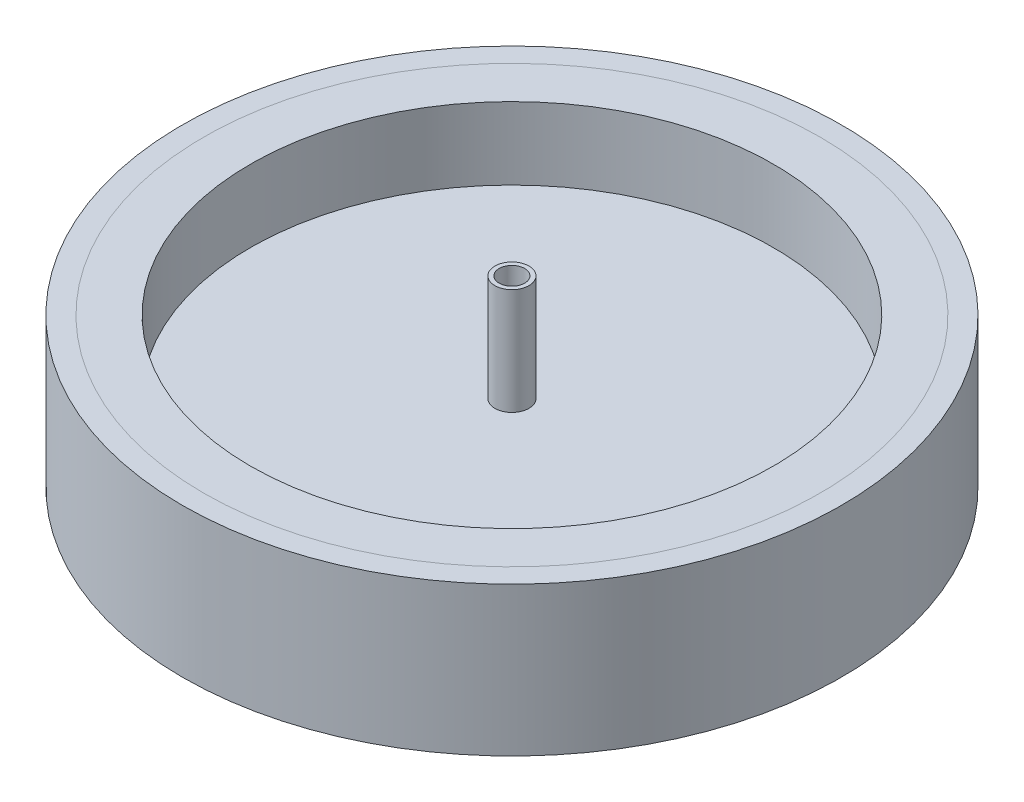
SolidWorks part; units mm, degrees
material "Rubber"
ref_plane "Front Plane" through (0, 0, 0) normal (0, 0, 1) x (1, 0, 0)
ref_plane "Top Plane" through (0, 0, 0) normal (0, 1, 0) x (1, 0, 0)
ref_plane "Right Plane" through (0, 0, 0) normal (1, 0, 0) x (0, 0, -1)
sketch "Sketch1" plane through (0, 0, 0) normal (0, 1, 0) x (1, 0, 0)
  circle A0 centre (0, 0) radius 72.5
  dimension "D1" = 145
extrude "Boss-Extrude1" add sketch "Sketch1" along normal blind 35
sketch "Sketch2" plane through (0, 35, 0) normal (0, 1, 0) x (1, 0, 0)
  circle A0 centre (0, 0) radius 61.5
  dimension "D1" = 123
extrude "Cut-Extrude2" cut sketch "Sketch2" against normal blind 17
sketch "Sketch4" plane through (0, 18, 0) normal (0, 1, 0) x (1, 0, 0)
  circle A0 centre (0, 0) radius 4
  dimension "D1" = 8
extrude "Boss-Extrude2" add sketch "Sketch4" along normal blind 25
sketch "Sketch5" plane through (0, 43, 0) normal (0, 1, 0) x (1, 0, 0)
  circle A0 centre (0, 0) radius 3
  dimension "D1" = 6
extrude "Cut-Extrude4" cut sketch "Sketch5" against normal blind 9
sketch "Sketch8" plane through (0, 0, 0) normal (0, 0, 1) x (1, 0, 0)
  line L0 (-72.5, 0) -> (-72.5, 35)
  line L1 (-72.5, 35) -> (-77.5, 35)
  line L2 (-77.5, 35) -> (-77.5, 0)
  line L3 (-77.5, 0) -> (-72.5, 0)
  line L4 (0, 40.5435) -> (0, -15.9756) construction
  dimension "D1" = 5
revolve "Revolve1" add sketch "Sketch8" angle 360 about L4
